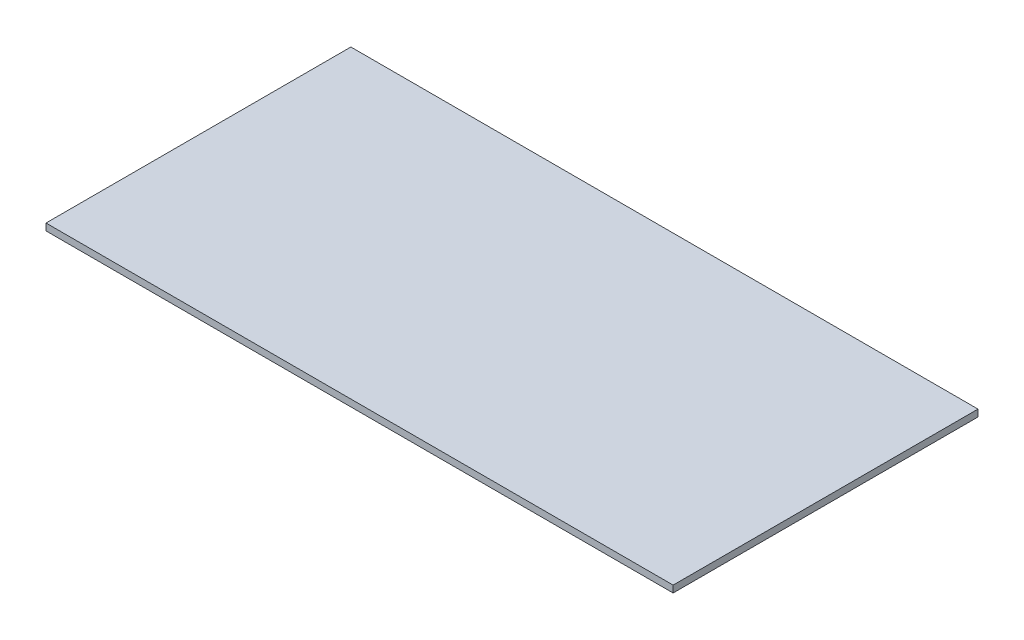
SolidWorks part; units mm, degrees
material "ABS"
ref_plane "Front Plane" through (0, 0, 0) normal (0, 0, 1) x (1, 0, 0)
ref_plane "Top Plane" through (0, 0, 0) normal (0, 1, 0) x (1, 0, 0)
ref_plane "Right Plane" through (0, 0, 0) normal (1, 0, 0) x (0, 0, -1)
sketch "Sketch1" plane through (0, 0, 0) normal (0, 1, 0) x (1, 0, 0)
  line L1 (228.6, -111.125) -> (-228.6, -111.125)
  line L2 (228.6, -111.125) -> (228.6, 111.125)
  line L3 (228.6, 111.125) -> (-228.6, 111.125)
  line L4 (-228.6, -111.125) -> (-228.6, 111.125)
  line L5 (228.6, -111.125) -> (-228.6, 111.125) construction
  line L6 (228.6, 111.125) -> (-228.6, -111.125) construction
  point P0 (0, 0)
  dimension "D1" = 457.2
  dimension "D2" = 222.25
extrude "Boss-Extrude1" add sketch "Sketch1" along normal blind 5
